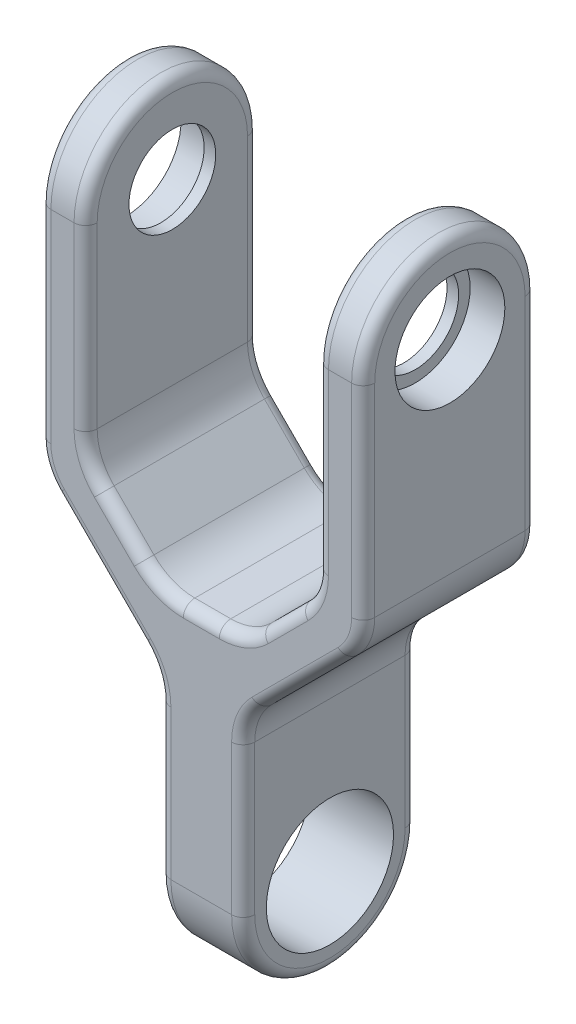
SolidWorks part; units mm, degrees
ref_plane "前视基准面" through (0, 0, 0) normal (0, 0, 1) x (1, 0, 0)
ref_plane "上视基准面" through (0, 0, 0) normal (0, 1, 0) x (1, 0, 0)
ref_plane "右视基准面" through (0, 0, 0) normal (1, 0, 0) x (0, 0, -1)
sketch "草图1" plane through (0, 0, 0) normal (0, 0, 1) x (1, 0, 0)
  line L0 (0, 0) -> (14.5, 0)
  line L1 (14.5, 0) -> (14.5, 30)
  line L2 (14.5, 30) -> (35.25, 50.75)
  line L3 (35.25, 50.75) -> (35.25, 90)
  line L4 (35.25, 90) -> (27.25, 90)
  line L5 (27.25, 90) -> (27.25, 55)
  line L6 (27.25, 55) -> (-12.75, 55)
  line L7 (-12.75, 55) -> (-12.75, 90)
  line L8 (-12.75, 90) -> (-20.75, 90)
  line L9 (-20.75, 90) -> (-20.75, 50.75)
  line L11 (0, 30) -> (0, 0)
  line L12 (0, 30) -> (-20.75, 50.75)
  line L13 (7.25, 0) -> (7.25, 40.1674) construction
  dimension "D1" = 135
  dimension "D2" = 135
  dimension "D3" = 14.5
  dimension "D4" = 8
  dimension "D5" = 8
  dimension "D6" = 40
  dimension "D7" = 90
  dimension "D8" = 30
  dimension "D9" = 35
extrude "凸台-拉伸1" add sketch "草图1" along normal blind 30
sketch "草图2" plane through (0, 0, 30) normal (0, 0, 1) x (1, 0, 0)
  line L0 (-12.75, 55) -> (0, 42.25)
  line L1 (0, 42.25) -> (14.5, 42.25)
  line L2 (14.5, 42.25) -> (27.25, 55)
  line L3 (-20.75, 50.75) -> (0, 30) construction
  line L4 (14.5, 30) -> (35.25, 50.75) construction
  line L5 (-12.75, 55) -> (27.25, 55)
extrude "切除-拉伸1" cut sketch "草图2" against normal through all
sketch "草图3" plane through (14.5, 0, 0) normal (1, 0, 0) x (0, 0, -1)
  line L0 (-30, 0) -> (0, 0)
  arc A0 (-30, 0) -> (0, 0) centre (-15, 0) ccw
extrude "凸台-拉伸2" add sketch "草图3" against normal up to surface (14.5 mm away) up to face at (0, 15, 15)
sketch "草图4" plane through (14.5, 0, 0) normal (1, 0, 0) x (0, 0, -1)
  circle A0 centre (-15, 0) radius 11
  dimension "D1" = 22
extrude "切除-拉伸2" cut sketch "草图4" against normal blind 20
sketch "草图5" plane through (14.5, 0, 0) normal (1, 0, 0) x (0, 0, -1)
  circle A0 centre (-15, 0) radius 9.5
  dimension "D1" = 19
extrude "切除-拉伸3" [suppressed] cut sketch "草图5" against normal blind 6
sketch "草图6" plane through (0, 0, 0) normal (-1, 0, 0) x (0, 0, 1)
  circle A0 centre (15, 0) radius 9.5
  dimension "D1" = 19
extrude "切除-拉伸4" [suppressed] cut sketch "草图6" against normal blind 6
sketch "草图7" plane through (35.25, 0, 0) normal (1, 0, 0) x (0, 0, -1)
  line L0 (-30, 90) -> (0, 90)
  arc A0 (-30, 90) -> (0, 90) centre (-15, 90) cw
extrude "凸台-拉伸3" add sketch "草图7" against normal up to surface (8 mm away) up to face at (27.25, 72.5, 15)
sketch "草图8" plane through (-20.75, 0, 0) normal (-1, 0, 0) x (0, 0, 1)
  line L0 (0, 90) -> (30, 90)
  arc A0 (0, 90) -> (30, 90) centre (15, 90) cw
extrude "凸台-拉伸4" add sketch "草图8" against normal up to surface (8 mm away) up to face at (-12.75, 72.5, 15)
sketch "草图9" plane through (-20.75, 0, 0) normal (-1, 0, 0) x (0, 0, 1)
  circle A0 centre (15, 90) radius 7.5
  dimension "D1" = 15
extrude "切除-拉伸5" cut sketch "草图9" against normal blind 62
sketch "草图10" plane through (-20.75, 0, 0) normal (-1, 0, 0) x (0, 0, 1)
  circle A0 centre (15, 90) radius 9.5
  dimension "D1" = 19
extrude "切除-拉伸6" cut sketch "草图10" against normal blind 6
sketch "草图11" plane through (35.25, 0, 0) normal (1, 0, 0) x (0, 0, -1)
  circle A0 centre (-15, 90) radius 9.5
  dimension "D1" = 19
extrude "切除-拉伸7" cut sketch "草图11" against normal blind 6
fillet "圆角1" radius 10 8 edges at (27.25, 55, 15) (14.5, 42.25, 15) (0, 42.25, 15) (-12.75, 55, 15) (-20.75, 50.75, 15) (0, 30, 15) (14.5, 30, 15) (35.25, 50.75, 15)
fillet "圆角2" radius 2 44 edges at (0, -15, 15) (14.5, -15, 15) (14.5, 12.9289, 30) (15.2612, 29.6847, 30) (24.875, 40.375, 30) (34.4888, 51.0653, 30) (35.25, 72.4461, 30) (27.25, 105, 15) (35.25, 105, 15) (27.25, 74.5711, 30) (26.4888, 55.3153, 30) (20.875, 48.625, 30) (14.1847, 43.0112, 30) (7.25, 42.25, 30) (0.3153, 43.0112, 30) (-6.375, 48.625, 30) (-11.9888, 55.3153, 30) (-12.75, 74.5711, 30) (-12.75, 105, 15) (-20.75, 105, 15) (-20.75, 72.4461, 30) (-19.9888, 51.0653, 30) (-10.375, 40.375, 30) (-0.7612, 29.6847, 30) (0, 12.9289, 30) (-0.7612, 29.6847, 0) (0, 12.9289, 0) (14.5, 12.9289, 0) (15.2612, 29.6847, 0) (24.875, 40.375, 0) (34.4888, 51.0653, 0) (35.25, 72.4461, 0) (27.25, 74.5711, 0) (26.4888, 55.3153, 0) (20.875, 48.625, 0) (14.1847, 43.0112, 0) (7.25, 42.25, 0) (0.3153, 43.0112, 0) (-6.375, 48.625, 0) (-11.9888, 55.3153, 0) (-12.75, 74.5711, 0) (-20.75, 72.4461, 0) (-19.9888, 51.0653, 0) (-10.375, 40.375, 0)
